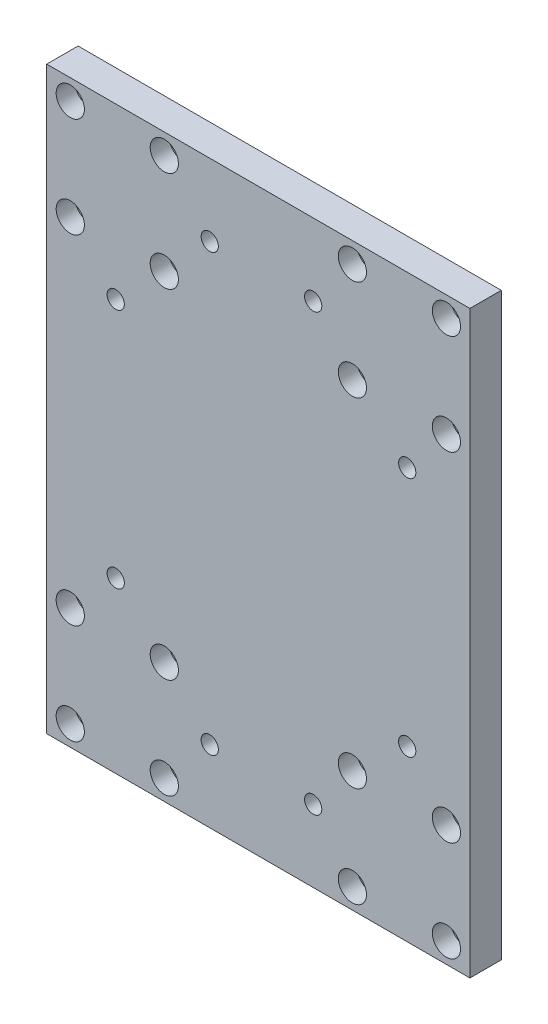
SolidWorks part; units mm, degrees
material "1.0037 (S235JR)"
ref_plane "Płaszczyzna przednia" through (0, 0, 0) normal (0, 0, 1) x (1, 0, 0)
ref_plane "Płaszczyzna górna" through (0, 0, 0) normal (0, 1, 0) x (1, 0, 0)
ref_plane "Płaszczyzna prawa" through (0, 0, 0) normal (1, 0, 0) x (0, 0, -1)
sketch "Szkic1" plane through (0, 0, 0) normal (0, 0, 1) x (1, 0, 0)
  line L1 (0, 0) -> (135, 0)
  line L2 (0, 0) -> (0, 185)
  line L3 (0, 185) -> (135, 185)
  line L4 (135, 0) -> (135, 185)
  dimension "D1" = 135
  dimension "D2" = 185
extrude "Dodanie-wyciągnięcie1" add sketch "Szkic1" along normal blind 10
sketch "Szkic2" plane through (0, 0, 10) normal (0, 0, 1) x (1, 0, 0)
  circle A0 centre (7.5, 178.5) radius 2.5 construction
  circle A1 centre (37.5, 178.5) radius 2.5 construction
  circle A2 centre (7.5, 146.5) radius 2.5 construction
  circle A3 centre (37.5, 146.5) radius 2.5 construction
  circle A4 centre (7.5, 38.5) radius 2.5 construction
  circle A5 centre (37.5, 38.5) radius 2.5 construction
  circle A6 centre (7.5, 6.5) radius 2.5 construction
  circle A7 centre (37.5, 6.5) radius 2.5 construction
  circle A8 centre (7.5, 178.5) radius 2.5
  circle A9 centre (37.5, 178.5) radius 2.5
  circle A10 centre (7.5, 146.5) radius 2.5
  circle A11 centre (37.5, 146.5) radius 2.5
  circle A12 centre (7.5, 38.5) radius 2.5
  circle A13 centre (37.5, 38.5) radius 2.5
  circle A14 centre (7.5, 6.5) radius 2.5
  circle A15 centre (37.5, 6.5) radius 2.5
hole_wizard "Pogłębienie walcowe pod M5 Wkręt do części metalowych z łbem sześciokątnym1" positions "Szkic4" profile "Szkic3" counterbore size "M5" standard "Ansi Metryczny" end condition through all
sketch "Szkic4" plane through (0, 0, 10) normal (0, 0, 1) x (1, 0, 0)
  line L0 (67.5, 185) -> (67.5, 0) construction
  line L1 (135, 185) -> (0, 185) construction
  line L2 (0, 0) -> (135, 0) construction
  point P0 (7.5, 178.5)
  point P1 (37.5, 178.5)
  point P4 (37.5, 146.5)
  point P7 (7.5, 146.5)
  point P10 (7.5, 38.5)
  point P13 (37.5, 38.5)
  point P16 (7.5, 6.5)
  point P19 (37.5, 6.5)
  point P33 (97.5, 6.5)
  point P34 (127.5, 6.5)
  point P35 (97.5, 38.5)
  point P36 (127.5, 38.5)
  point P37 (127.5, 146.5)
  point P38 (97.5, 146.5)
  point P39 (97.5, 178.5)
  point P40 (127.5, 178.5)
sketch "Szkic3" plane through (7.5, 178.5, 10) normal (1, 0, 0) x (0, -1, 0)
  line L0 (0, 0) -> (0, 10)
  line L1 (0, 10) -> (2.75, 10)
  line L3 (2.75, 10) -> (2.75, 6)
  line L4 (2.75, 6) -> (4.5, 6)
  line L5 (4.5, 6) -> (4.5, 0)
  line L7 (4.5, 0) -> (0, 0)
  line L11 (0, -6.35) -> (0, 107.95) construction
  dimension "Średnica otworu na wylot" = 5.5
  dimension "Głębokość otworu na wylot" = 10
  dimension "Średnica pogłębienia walcowego" = 9
  dimension "Głębokość pogłębienia walcowego" = 6
sketch "Szkic5" plane through (0, 0, 10) normal (0, 0, 1) x (1, 0, 0)
  line L0 (-30.7056, 92.5) -> (135, 92.5) construction
  line L2 (135, 0) -> (135, 185) construction
  circle A0 centre (22, 54) radius 2.75
  circle A1 centre (52, 23) radius 2.75
  circle A2 centre (85, 23) radius 2.75
  circle A3 centre (115, 54) radius 2.75
  circle A4 centre (115, 54) radius 2.75 construction
  circle A5 centre (85, 23) radius 2.75 construction
  circle A6 centre (52, 23) radius 2.75 construction
  circle A7 centre (22, 54) radius 2.75 construction
  circle A8 centre (52, 162) radius 2.75
  circle A9 centre (22, 131) radius 2.75
  circle A10 centre (115, 131) radius 2.75
  circle A11 centre (85, 162) radius 2.75
extrude "Wytnij-wyciągnięcie1" cut sketch "Szkic5" against normal through all
